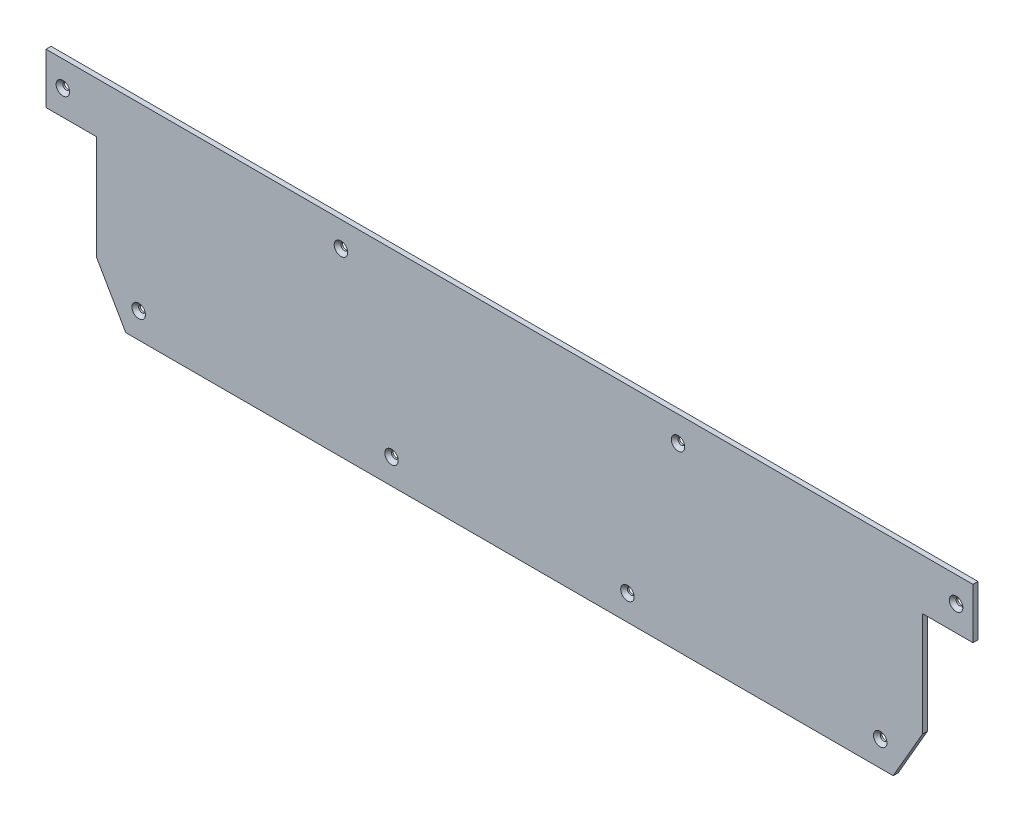
SolidWorks part; units mm, degrees
material "1060 合金"
ref_plane "前视基准面" through (0, 0, 0) normal (0, 0, 1) x (1, 0, 0)
ref_plane "上视基准面" through (0, 0, 0) normal (0, 1, 0) x (1, 0, 0)
ref_plane "右视基准面" through (0, 0, 0) normal (1, 0, 0) x (0, 0, -1)
sketch "草图1" plane through (0, 0, 0) normal (0, 0, 1) x (1, 0, 0)
  line L1 (-275, 61) -> (275, 61)
  line L2 (-275, 61) -> (-275, -61)
  line L3 (-275, -61) -> (275, -61)
  line L4 (275, 61) -> (275, -61)
  point P4 (0, -61)
  point P6 (-275, 0)
  dimension "D1" = 122
  dimension "D2" = 550
extrude "凸台-拉伸1" add sketch "草图1" along normal blind 3
sketch "草图3" plane through (0, 0, 3) normal (0, 0, 1) x (1, 0, 0)
  line L0 (-275, 61) -> (-275, -61) construction
  line L1 (-275, 31) -> (-245, 31)
  line L2 (-275, 31) -> (-275, -61)
  line L3 (-275, -61) -> (-227.6795, -61)
  line L4 (-245, 31) -> (-245, -31)
  line L5 (-275, -61) -> (275, -61) construction
  line L6 (-245, -31) -> (-227.6795, -61)
  line L7 (0, 61) -> (0, -61) construction
  line L8 (275, 61) -> (-275, 61) construction
  line L9 (245, -31) -> (227.6795, -61)
  line L10 (245, 31) -> (245, -31)
  line L11 (275, -61) -> (227.6795, -61)
  line L12 (275, 31) -> (275, -61)
  line L13 (275, 31) -> (245, 31)
  dimension "D1" = 30
  dimension "D2" = 30
  dimension "D3" = 60
  dimension "D4" = 30
extrude "切除-拉伸2" cut sketch "草图3" against normal through all
sketch "草图2" plane through (0, 0, 0) normal (0, 0, 1) x (1, 0, 0)
  line L0 (275, 61) -> (-275, 61) construction
  line L1 (0, 0) -> (0, -74.9984) construction
  line L2 (-275, 61) -> (-275, 31) construction
  line L3 (-227.6795, -61) -> (227.6795, -61) construction
  line L4 (-245, -31) -> (-245, 31) construction
  circle A0 centre (-100, 46) radius 2
  circle A1 centre (-265, 46) radius 2
  circle A2 centre (265, 46) radius 2
  circle A3 centre (100, 46) radius 2
  circle A4 centre (-220, -46) radius 2
  circle A5 centre (-70, -46) radius 2
  circle A6 centre (70, -46) radius 2
  circle A7 centre (220, -46) radius 2
  dimension "D2" = 4
  dimension "D1" = 10
  dimension "D3" = 100
  dimension "D4" = 15
  dimension "D5" = 15
  dimension "D6" = 25
  dimension "D7" = 70
extrude "切除-拉伸1" cut sketch "草图2" along normal blind 10
chamfer "倒角1" distance 2 angle 45 8 edges at (72, -46, 3) (222, -46, 3) (267, 46, 3) (102, 46, 3) (-68, -46, 3) (-218, -46, 3) (-98, 46, 3) (-263, 46, 3)
